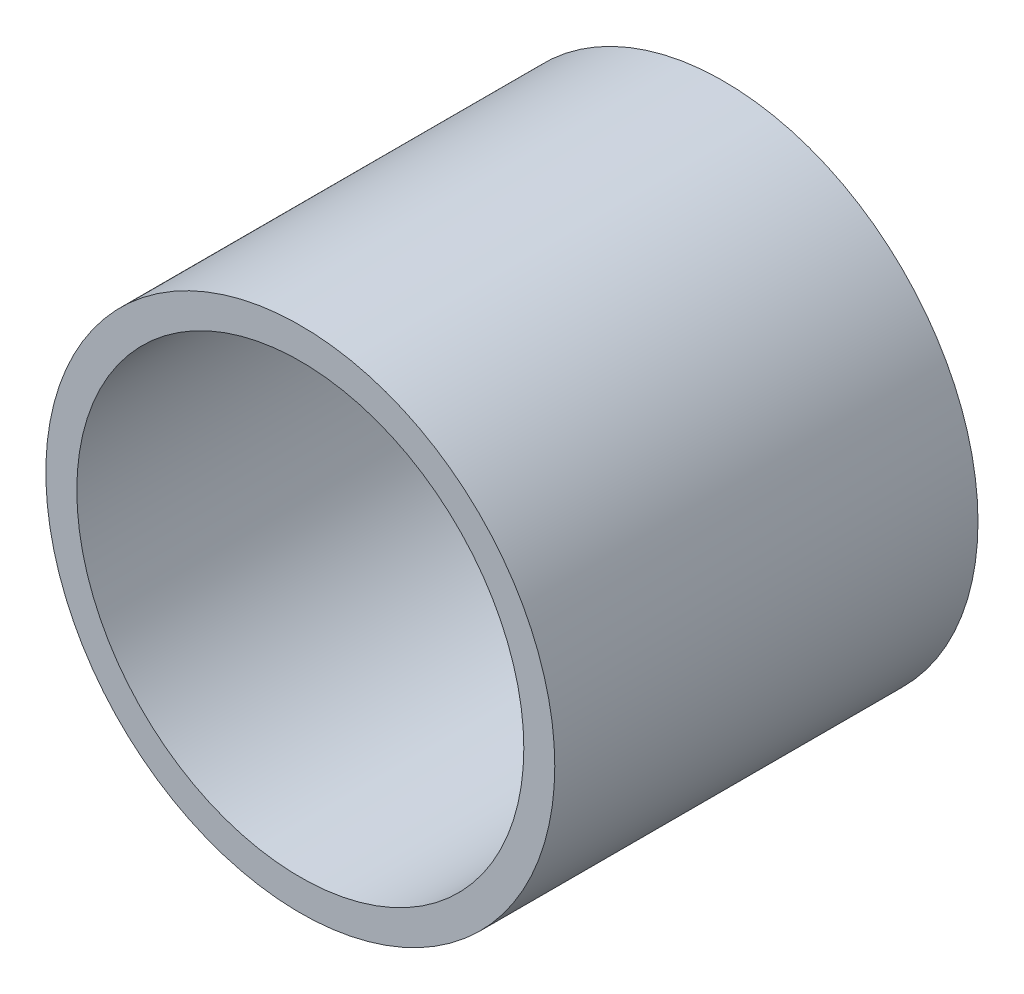
SolidWorks part; units mm, degrees
material "TPU 95A"
ref_plane "Front Plane" through (0, 0, 0) normal (1, 0, 0) x (0, 1, 0)
ref_plane "Top Plane" through (0, 0, 0) normal (0, 0, 1) x (0, 1, 0)
ref_plane "Right Plane" through (0, 0, 0) normal (0, 1, 0) x (-1, 0, 0)
sketch "Sketch1" plane through (0, 0, 0) normal (0, 0, 1) x (0, 1, 0)
  circle A0 centre (0, 0) radius 5.5
  circle A1 centre (0, 0) radius 6.262
  dimension "D1" = 11
  dimension "D2" = 12.524
extrude "Boss-Extrude1" add sketch "Sketch1" along normal blind 10.414
equation "\"D2@Sketch1\"=11mm+0.06in"
